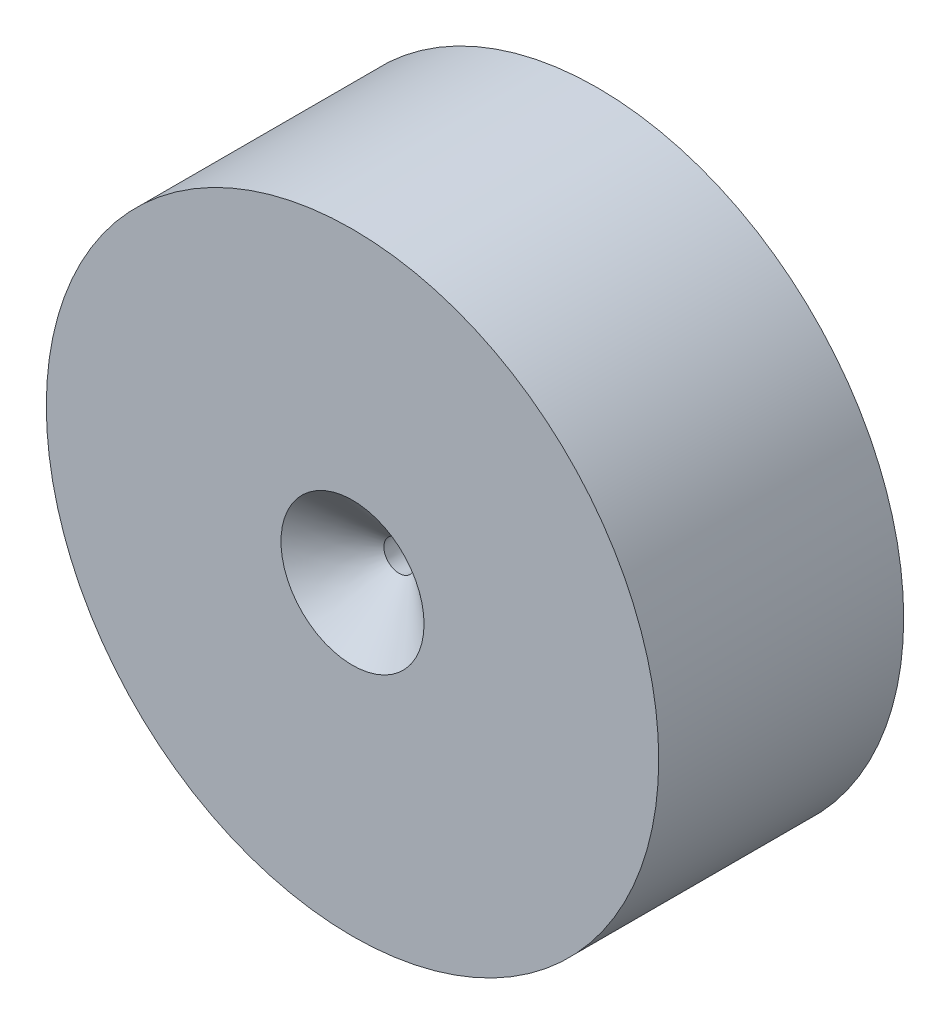
SolidWorks part; units mm, degrees
material "Copper"
ref_plane "Front Plane" through (0, 0, 0) normal (0, 0, 1) x (1, 0, 0)
ref_plane "Top Plane" through (0, 0, 0) normal (0, 1, 0) x (1, 0, 0)
ref_plane "Right Plane" through (0, 0, 0) normal (1, 0, 0) x (0, 0, -1)
sketch "Sketch1" plane through (0, 0, 0) normal (0, 0, 1) x (1, 0, 0)
  circle A0 centre (0, 0) radius 5
  dimension "D1" = 10
extrude "Boss-Extrude1" add sketch "Sketch1" along normal blind 4
ref_plane "Plane1" through (0, 0, 0) normal (1, 0, 0) x (0, 0, -1)
sketch "Sketch2" plane through (0, 0, 0) normal (1, 0, 0) x (0, 0, -1)
  line L0 (-4, 1.1681) -> (-3.2379, 0.25)
  line L2 (-4, 5) -> (-4, -5) construction
  line L4 (-3.2379, 0.25) -> (-1.3078, 0.5)
  line L5 (-1.3078, 0.5) -> (0, 2)
  line L7 (0, -5) -> (0, 5) construction
  line L8 (0, 2) -> (0, 0)
  line L9 (-4, 1.1681) -> (-4, 0)
  line L10 (-4, 0) -> (0, 0) construction
  line L11 (0, 0) -> (-5.1364, 0) construction
  line L12 (-5.1364, 0) -> (1.5474, 0) construction
  line L13 (0, 0) -> (-4, 0)
  dimension "D1" = 0.5
  dimension "D2" = 0.25
  dimension "D3" = 1.1681
  dimension "D4" = 2
revolve "Cut-Revolve1" cut sketch "Sketch2" angle 360 about L11
